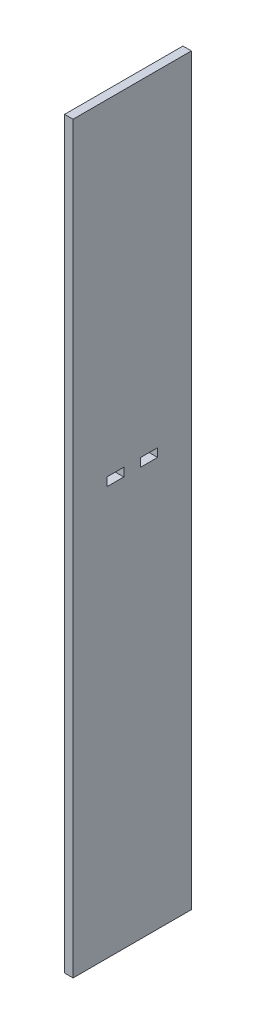
SolidWorks part; units mm, degrees
ref_plane "Front Plane" through (0, 0, 0) normal (0, 0, 1) x (1, 0, 0)
ref_plane "Top Plane" through (0, 0, 0) normal (0, 1, 0) x (1, 0, 0)
ref_plane "Right Plane" through (0, 0, 0) normal (1, 0, 0) x (0, 0, -1)
sketch "Sketch2" plane through (0, 0, 0) normal (0, 1, 0) x (1, 0, 0)
  line L1 (-38.1, -44.45) -> (-44.45, -44.45)
  line L2 (-38.1, -44.45) -> (-38.1, 44.45)
  line L3 (-38.1, 44.45) -> (-44.45, 44.45)
  line L4 (-44.45, -44.45) -> (-44.45, 44.45)
  dimension "D1" = 6.35
  dimension "D2" = 88.9
extrude "Boss-Extrude1" add sketch "Sketch2" along normal blind 558.8
sketch "Sketch3" plane through (-44.45, 0, 0) normal (-1, 0, 0) x (0, 0, 1)
  line L0 (0, 558.8) -> (0, 0) construction
  line L1 (-19.05, 313.305) -> (-6.35, 313.305)
  line L2 (-19.05, 313.305) -> (-19.05, 306.955)
  line L3 (-19.05, 306.955) -> (-6.35, 306.955)
  line L4 (-6.35, 313.305) -> (-6.35, 306.955)
  line L5 (6.35, 313.305) -> (19.05, 313.305)
  line L6 (6.35, 313.305) -> (6.35, 306.955)
  line L7 (6.35, 306.955) -> (19.05, 306.955)
  line L8 (19.05, 313.305) -> (19.05, 306.955)
  line L9 (-44.45, 558.8) -> (44.45, 558.8) construction
  line L10 (0, 310.13) -> (38.2669, 310.13) construction
  line L11 (-39.2518, 306.955) -> (48.5256, 306.955) construction
  dimension "D1" = 12.7
  dimension "D2" = 6.35
  dimension "D3" = 6.35
  dimension "D4" = 12.7
  dimension "D5" = 12.7
extrude "Cut-Extrude1" cut sketch "Sketch3" against normal through all
